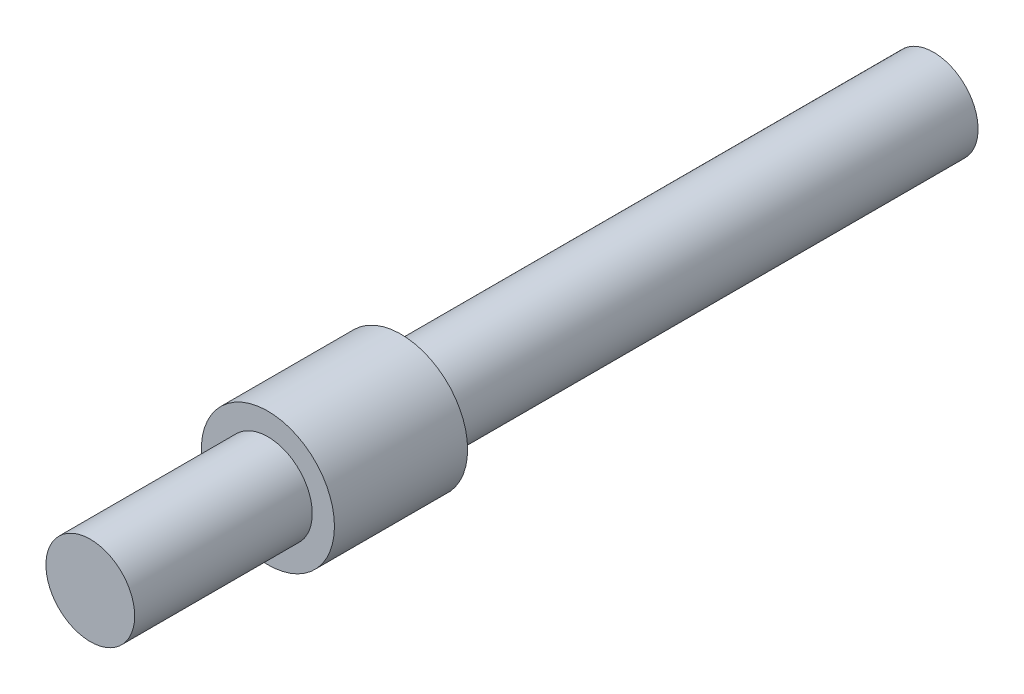
SolidWorks part; units mm, degrees
ref_plane "Front Plane" through (0, 0, 0) normal (0, 0, 1) x (1, 0, 0)
ref_plane "Top Plane" through (0, 0, 0) normal (0, 1, 0) x (1, 0, 0)
ref_plane "Right Plane" through (0, 0, 0) normal (1, 0, 0) x (0, 0, -1)
sketch "Sketch1" plane through (0, 0, 0) normal (0, 0, 1) x (1, 0, 0)
  circle A0 centre (0, 0) radius 2
  dimension "D1" = 4
extrude "Boss-Extrude1" add sketch "Sketch1" along normal blind 24
ref_plane "Plane1" through (0, 0, 10) normal (0, 0, -1) x (-1, 0, 0)
ref_plane "Plane2" through (0, 0, 19) normal (0, 0, 1) x (1, 0, 0)
sketch "Sketch3" plane through (0, 0, 19) normal (0, 0, 1) x (1, 0, 0)
  circle A0 centre (0, 0) radius 3
  dimension "D1" = 6
extrude "Boss-Extrude3" add sketch "Sketch3" against normal up to surface (9 mm away) up to plane "Plane1"
sketch "Sketch4" plane through (0, 0, 0) normal (0, 0, -1) x (-1, 0, 0)
  circle A0 centre (0, 0) radius 2
extrude "Boss-Extrude4" add sketch "Sketch4" along normal blind 14
sketch "Sketch5" plane through (0, 0, 19) normal (0, 0, 1) x (1, 0, 0)
  circle A0 centre (0, 0) radius 4
  circle A1 centre (0, 0) radius 2
extrude "Cut-Extrude1" cut sketch "Sketch5" against normal blind 3
